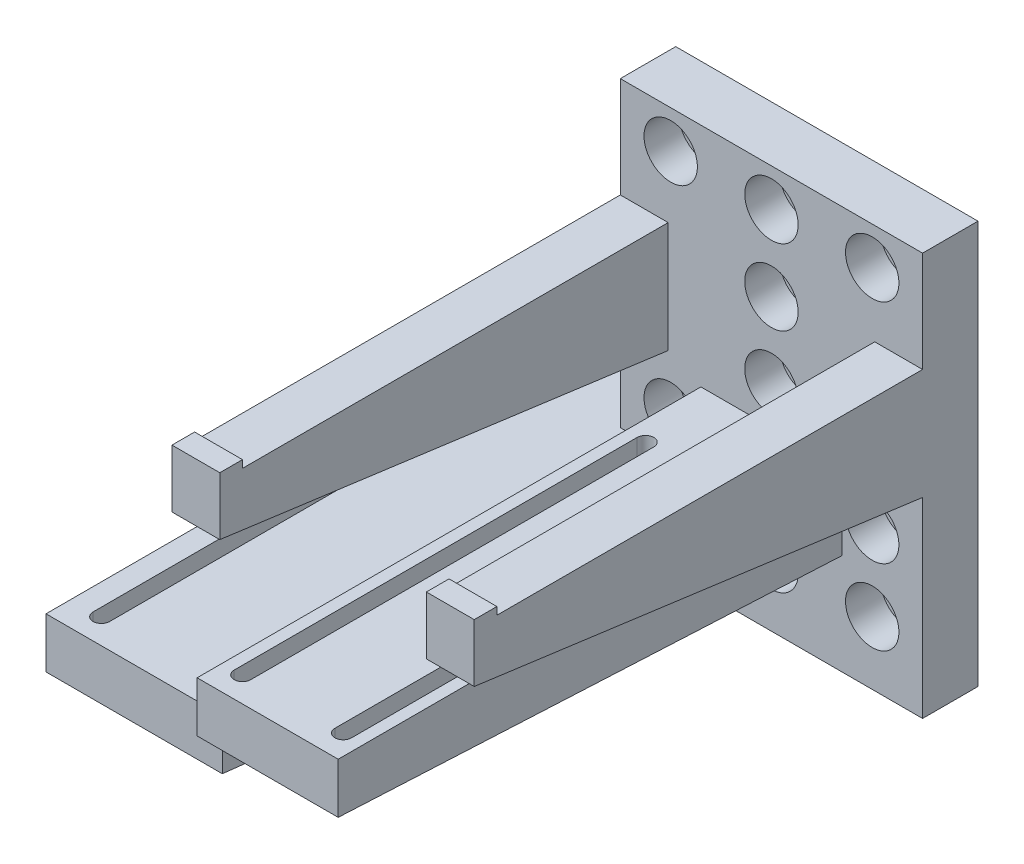
SolidWorks part; units mm, degrees
ref_plane "Front Plane" through (0, 0, 0) normal (0, 0, 1) x (1, 0, 0)
ref_plane "Top Plane" through (0, 0, 0) normal (0, 1, 0) x (1, 0, 0)
ref_plane "Right Plane" through (0, 0, 0) normal (1, 0, 0) x (0, 0, -1)
sketch "Sketch1" plane through (0, 0, 0) normal (0, 0, 1) x (1, 0, 0)
  line L0 (-20, 40) -> (-20, -40) construction
  line L1 (-30, 40) -> (30, 40)
  line L2 (-30, 40) -> (-30, -40)
  line L3 (-30, -40) -> (30, -40)
  line L4 (30, 40) -> (30, -40)
  line L5 (20, 40) -> (20, -40) construction
  line L6 (0, 40) -> (0, -40) construction
  line L7 (30, 32.5) -> (-30, 32.5) construction
  line L8 (-30, 2.5) -> (30, 2.5) construction
  line L9 (-30, -12.5) -> (30, -12.5) construction
  line L10 (-30, 17.5) -> (30, 17.5) construction
  line L11 (-30, -27.5) -> (30, -27.5) construction
  circle A0 centre (-20, -12.5) radius 3.3
  circle A2 centre (20, -12.5) radius 3.3
  circle A3 centre (0, 17.5) radius 3.3
  circle A4 centre (0, 2.5) radius 3.3
  circle A5 centre (20, 32.5) radius 3.3
  circle A6 centre (0, 32.5) radius 3.3
  circle A7 centre (-20, 32.5) radius 3.3
  circle A9 centre (0, -27.5) radius 3.3
  circle A10 centre (20, -27.5) radius 3.3
  point P31 (0, 0)
  dimension "D3" = 6.6
  dimension "D1" = 60
  dimension "D2" = 80
  dimension "D4" = 27.5
  dimension "D5" = 15
  dimension "D6" = 15
  dimension "D7" = 20
  dimension "D8" = 20
  dimension "D9" = 15
  dimension "D10" = 15
extrude "Boss-Extrude1" add sketch "Sketch1" against normal blind 4
sketch "Sketch3" plane through (0, 0, 0) normal (0, 0, 1) x (1, 0, 0)
  line L0 (-30, -40) -> (30, -40) construction
  line L1 (-30, 40) -> (30, 40)
  line L2 (-30, 40) -> (-30, -40)
  line L3 (-30, -40) -> (30, -40)
  line L4 (30, 40) -> (30, -40)
  line L5 (30, -40) -> (30, 40) construction
  circle A0 centre (0, 17.5) radius 5.3
  circle A1 centre (-20, -12.5) radius 5.3
  circle A2 centre (20, -12.5) radius 5.3
  circle A4 centre (0, 2.5) radius 5.3
  circle A5 centre (-20, 32.5) radius 5.3
  circle A6 centre (0, 32.5) radius 5.3
  circle A7 centre (20, 32.5) radius 5.3
  circle A9 centre (0, -27.5) radius 5.3
  circle A10 centre (20, -27.5) radius 5.3
  dimension "D1" = 10.6
extrude "Boss-Extrude2" add sketch "Sketch3" along normal blind 7
sketch "Sketch4" plane through (0, 0, 7) normal (0, 0, 1) x (1, 0, 0)
  line L0 (-30, 20) -> (30, 20) construction
  line L1 (-30, 20) -> (-20.5, 20)
  line L2 (-30, 20) -> (-30, 10)
  line L3 (-30, 10) -> (-20.5, 10)
  line L4 (-20.5, 20) -> (-20.5, 10)
  line L5 (20.5, 20) -> (30, 20)
  line L6 (20.5, 20) -> (20.5, 10)
  line L7 (20.5, 10) -> (30, 10)
  line L8 (30, 20) -> (30, 10)
  line L9 (-30, 40) -> (-30, -40) construction
  line L10 (30, -40) -> (30, 40) construction
  line L11 (30, 40) -> (-30, 40) construction
  line L12 (0, 40) -> (0, -25) construction
  dimension "D1" = 9.5
  dimension "D2" = 9.5
  dimension "D3" = 10
  dimension "D4" = 10
  dimension "D5" = 20
extrude "Boss-Extrude3" add sketch "Sketch4" along normal blind 89
sketch "Sketch5" plane through (30, 0, 0) normal (1, 0, 0) x (0, 0, -1)
  line L0 (-96, 10) -> (-7, 10)
  line L1 (-7, 10) -> (-7, -2)
  line L2 (-7, -40) -> (-7, 10) construction
  line L3 (-7, -2) -> (-96, 10)
  dimension "D1" = 12
extrude "Boss-Extrude4" add sketch "Sketch5" against normal blind 9.5
sketch "Sketch6" plane through (-30, 0, 0) normal (-1, 0, 0) x (0, 0, 1)
  line L0 (96, 10) -> (7, 10)
  line L1 (7, 10) -> (7, -2)
  line L2 (7, 10) -> (7, -40) construction
  line L3 (7, -2) -> (96, 10)
  dimension "D1" = 12
extrude "Boss-Extrude5" add sketch "Sketch6" against normal blind 9.5
sketch "Sketch7" plane through (0, 20, 0) normal (0, 1, 0) x (1, 0, 0)
  line L0 (-20.5, -96) -> (-20.5, -7) construction
  line L1 (-30, -96) -> (-20.5, -96)
  line L2 (-30, -96) -> (-30, -91.5)
  line L3 (-30, -91.5) -> (-20.5, -91.5)
  line L4 (-20.5, -96) -> (-20.5, -91.5)
  line L5 (30, -96) -> (30, -7) construction
  line L6 (20.5, -96) -> (30, -96)
  line L7 (20.5, -96) -> (20.5, -91.5)
  line L8 (20.5, -91.5) -> (30, -91.5)
  line L9 (30, -96) -> (30, -91.5)
  dimension "D1" = 4.5
  dimension "D2" = 4.5
extrude "Boss-Extrude6" add sketch "Sketch7" along normal blind 1.5
sketch "Sketch9" plane through (0, 0, 7) normal (0, 0, 1) x (1, 0, 0)
  line L1 (-14, -5) -> (14, -5)
  line L2 (-14, -5) -> (-14, -15)
  line L3 (-14, -15) -> (14, -15)
  line L4 (14, -5) -> (14, -15)
  line L5 (0, 40) -> (0, -15) construction
  line L6 (30, 40) -> (-30, 40) construction
  dimension "D1" = 10
  dimension "D2" = 28
  dimension "D3" = 14
  dimension "D4" = 25
extrude "Boss-Extrude7" add sketch "Sketch9" along normal blind 100
sketch "Sketch11" plane through (-14, 0, 0) normal (-1, 0, 0) x (0, 0, 1)
  line L0 (107, -15) -> (7, -15)
  line L1 (7, -15) -> (7, -20)
  line L2 (7, -20) -> (107, -15)
  dimension "D1" = 5
extrude "Boss-Extrude9" add sketch "Sketch11" against normal blind 28
sketch "Sketch12" plane through (0, -5, 0) normal (0, 1, 0) x (1, 0, 0)
  line L0 (10, -7) -> (10, -107) construction
  line L1 (14, -7) -> (-14, -7) construction
  line L2 (14, -107) -> (-14, -107) construction
  line L3 (10, -107) -> (-10, -107) construction
  line L4 (-10, -107) -> (-10, -7) construction
  line L5 (0, -7) -> (0, -107) construction
  line L6 (-14, -102) -> (14, -102) construction
  line L7 (-14, -107) -> (-14, -7) construction
  line L8 (14, -107) -> (14, -7) construction
  line L9 (-10, -22) -> (10, -22) construction
  line L10 (-11.65, -22) -> (-11.65, -102)
  line L11 (8.35, -22) -> (11.65, -22) construction
  line L12 (-8.35, -102) -> (-8.35, -22)
  line L13 (8.35, -22) -> (8.35, -102)
  line L15 (11.65, -102) -> (11.65, -22)
  arc A0 (-11.65, -102) -> (-8.35, -102) centre (-10, -102) ccw
  arc A1 (8.35, -102) -> (11.65, -102) centre (10, -102) ccw
  arc A2 (-8.35, -22) -> (-11.65, -22) centre (-10, -22) ccw
  arc A3 (11.65, -22) -> (8.35, -22) centre (10, -22) ccw
  dimension "D5" = 3.3
  dimension "D1" = 20
  dimension "D2" = 10
  dimension "D3" = 15
  dimension "D4" = 5
extrude "Cut-Extrude1" cut sketch "Sketch12" against normal blind 18
sketch "Sketch13" plane through (-30, 0, 0) normal (-1, 0, 0) x (0, 0, 1)
  line L1 (91.5, 20) -> (7, 20) construction
  line L2 (-4, -20) -> (96, -20)
  line L3 (-4, -20) -> (-4, -30)
  line L4 (-4, -30) -> (96, -30)
  line L5 (96, -20) -> (96, -30)
  line L8 (96, 21.5) -> (96, 10) construction
  line L9 (-4, 40) -> (-4, -40) construction
  dimension "D1" = 40
  dimension "D2" = 10
extrude "Boss-Extrude10" add sketch "Sketch13" along normal blind 25 and the other way blind 10 separate body
sketch "Sketch14" plane through (-30, 0, 0) normal (-1, 0, 0) x (0, 0, 1)
  line L1 (-4, -20) -> (7, -20)
  line L2 (-4, -20) -> (-4, -40)
  line L3 (-4, -40) -> (7, -40)
  line L4 (7, -20) -> (7, -40)
  dimension "D1" = 20
  dimension "D2" = 11
extrude "Boss-Extrude11" add sketch "Sketch14" along normal blind 25
sketch "Sketch15" plane through (0, -20, 0) normal (0, 1, 0) x (1, 0, 0)
  line L0 (-49, -7) -> (-49, -96) construction
  line L1 (-20, -7) -> (-30, -7) construction
  line L2 (-20, -96) -> (-55, -96) construction
  line L3 (-55, -96) -> (-55, 4) construction
  line L4 (-49, -17) -> (-55, -17) construction
  line L5 (-49, -91) -> (-55, -91) construction
  line L6 (-50.65, -91) -> (-50.65, -17)
  line L7 (-47.352, -17.0809) -> (-47.352, -91.0809)
  circle A0 centre (-49, -17) radius 1.65 construction
  circle A1 centre (-49, -91) radius 1.65 construction
  arc A2 (-50.65, -17) -> (-47.352, -17.0809) centre (-49, -17) cw
  arc A3 (-50.65, -91) -> (-47.352, -91.0809) centre (-49, -91) ccw
  dimension "D2" = 3.3
  dimension "D3" = 3.3
  dimension "D5" = 5
  dimension "D1" = 6
  dimension "D4" = 10
extrude "Cut-Extrude2" cut sketch "Sketch15" against normal blind 10
sketch "Sketch16" plane through (-20, 0, 0) normal (1, 0, 0) x (0, 0, -1)
  line L0 (-96, -30) -> (-7, -30)
  line L1 (-7, -30) -> (-7, -40)
  line L2 (-7, -40) -> (-96, -30)
extrude "Boss-Extrude12" add sketch "Sketch16" against normal blind 15
